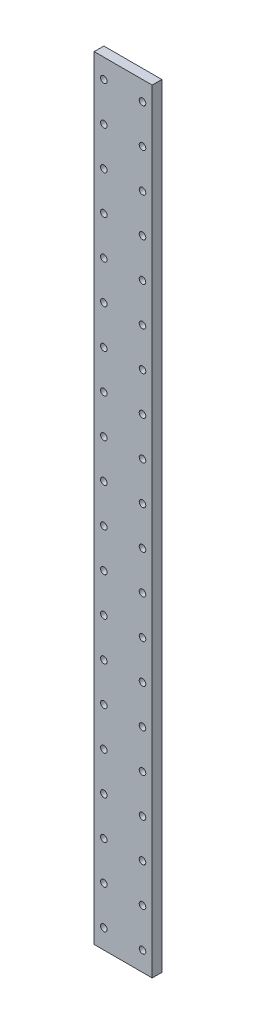
SolidWorks part; units mm, degrees
ref_plane "Front Plane" through (0, 0, 0) normal (0, 0, 1) x (1, 0, 0)
ref_plane "Top Plane" through (0, 0, 0) normal (0, 1, 0) x (1, 0, 0)
ref_plane "Right Plane" through (0, 0, 0) normal (1, 0, 0) x (0, 0, -1)
sketch "Sketch1" plane through (0, 0, 0) normal (0, 0, 1) x (1, 0, 0)
  line L1 (-19.05, -254) -> (19.05, -254)
  line L2 (-19.05, -254) -> (-19.05, 254)
  line L3 (-19.05, 254) -> (19.05, 254)
  line L4 (19.05, -254) -> (19.05, 254)
  line L5 (-19.05, -254) -> (19.05, 254) construction
  line L6 (-19.05, 254) -> (19.05, -254) construction
  point P0 (0, 0)
  dimension "D1" = 38.1
  dimension "D2" = 508
extrude "Boss-Extrude1" add sketch "Sketch1" along normal mid plane 6.35
hole_wizard "#8 Clearance Hole1" positions "Sketch3" profile "Sketch2" hole size "#8" standard "ANSI Inch" end condition through all
sketch "Sketch3" plane through (0, 0, 3.175) normal (0, 0, 1) x (1, 0, 0)
  line L0 (-19.05, -254) -> (19.05, -254) construction
  line L1 (0, -254) -> (0, 49746) construction
  point P16 (0, -254)
  point P28 (-12.7, -241.3)
  point P30 (12.7, -241.3)
  point P46 (-12.7, -215.9)
  point P47 (12.7, -215.9)
  point P48 (-12.7, -190.5)
  point P49 (12.7, -190.5)
  point P50 (-12.7, -165.1)
  point P51 (12.7, -165.1)
  point P52 (-12.7, -139.7)
  point P53 (12.7, -139.7)
  point P54 (-12.7, -114.3)
  point P55 (12.7, -114.3)
  point P56 (-12.7, -88.9)
  point P57 (12.7, -88.9)
  point P58 (-12.7, -63.5)
  point P59 (12.7, -63.5)
  point P60 (-12.7, -38.1)
  point P61 (12.7, -38.1)
  point P62 (-12.7, -12.7)
  point P63 (12.7, -12.7)
  point P64 (-12.7, 12.7)
  point P65 (12.7, 12.7)
  point P66 (-12.7, 38.1)
  point P67 (12.7, 38.1)
  point P68 (-12.7, 63.5)
  point P69 (12.7, 63.5)
  point P70 (-12.7, 88.9)
  point P71 (12.7, 88.9)
  point P72 (-12.7, 114.3)
  point P73 (12.7, 114.3)
  point P82 (-12.7, 139.7)
  point P83 (12.7, 139.7)
  point P84 (-12.7, 165.1)
  point P85 (12.7, 165.1)
  point P86 (-12.7, 190.5)
  point P87 (12.7, 190.5)
  point P88 (-12.7, 215.9)
  point P89 (12.7, 215.9)
  point P90 (-12.7, 241.3)
  point P91 (12.7, 241.3)
  dimension "D1" = 25.4
  dimension "D2" = 12.7
  dimension "D4" = 25.4
  dimension "D3" = 20
sketch "Sketch2" plane through (-12.7, -241.3, 3.175) normal (1, 0, 0) x (0, -1, 0)
  line L0 (0, 0) -> (0, 6.35)
  line L1 (0, 6.35) -> (2.1526, 6.35)
  line L2 (2.1526, 6.35) -> (2.1526, 0)
  line L5 (2.1526, 0) -> (0, 0)
  line L11 (0, -6.35) -> (0, 107.95) construction
  dimension "Thru Hole Dia." = 4.3053
  dimension "Thru Hole Depth" = 6.35
